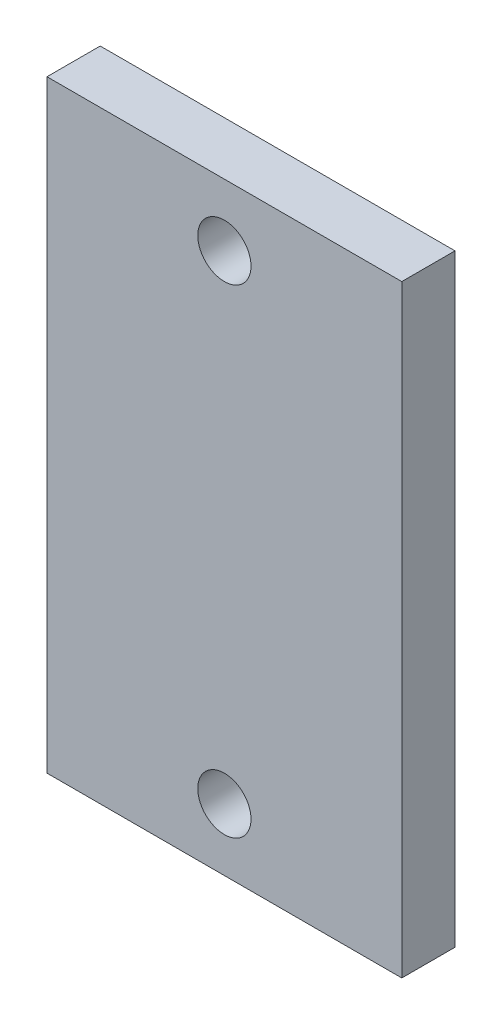
SolidWorks part; units mm, degrees
ref_plane "Plan de face" through (0, 0, 0) normal (0, 0, 1) x (1, 0, 0)
ref_plane "Plan de dessus" through (0, 0, 0) normal (0, 1, 0) x (1, 0, 0)
ref_plane "Plan de droite" through (0, 0, 0) normal (1, 0, 0) x (0, 0, -1)
sketch "Esquisse1" plane through (0, 0, 0) normal (0, 0, 1) x (1, 0, 0)
  line L1 (-8.276, 6.8468) -> (11.724, 6.8468)
  line L2 (-8.276, 6.8468) -> (-8.276, -27.1532)
  line L3 (-8.276, -27.1532) -> (11.724, -27.1532)
  line L4 (11.724, 6.8468) -> (11.724, -27.1532)
  circle A0 centre (1.724, 3.3468) radius 1.5
  circle A1 centre (1.724, -23.6532) radius 1.5
  dimension "D4" = 3.5
  dimension "D5" = 10
  dimension "D1" = 20
  dimension "D2" = 34
  dimension "D3" = 27
extrude "Boss.-Extru.1" add sketch "Esquisse1" along normal blind 3
